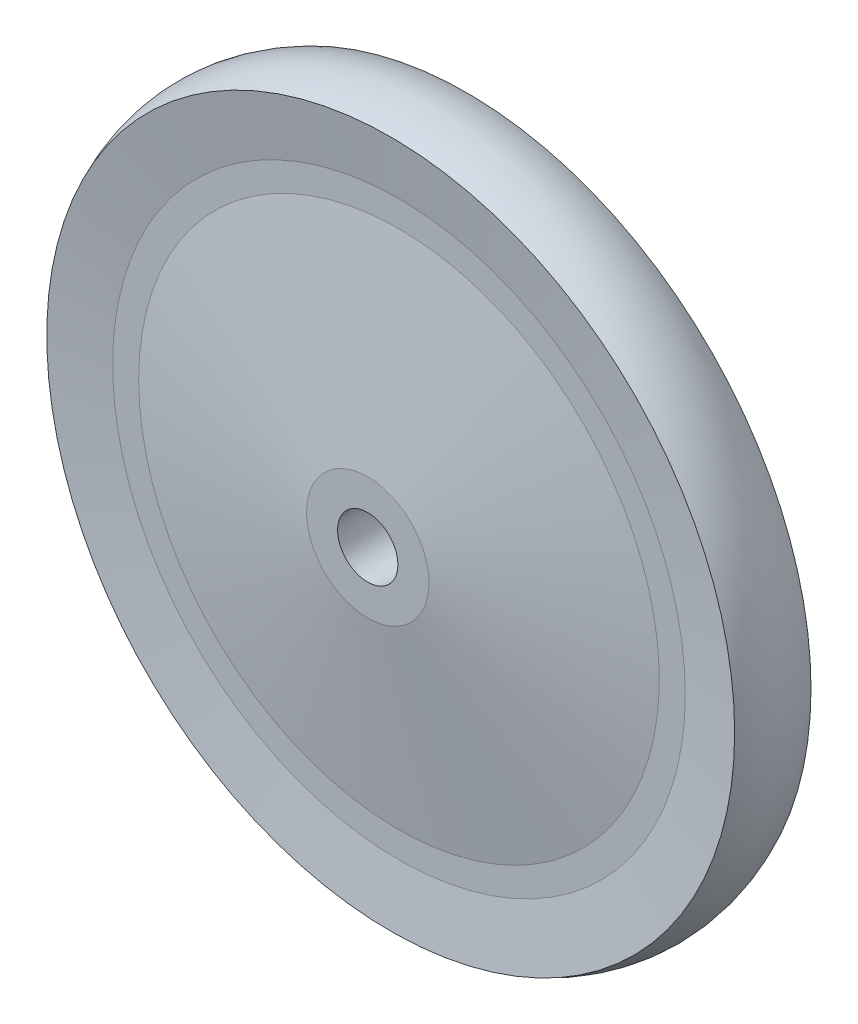
SolidWorks part; units mm, degrees
ref_plane "Front Plane" through (0, 0, 0) normal (0, 0, 1) x (1, 0, 0)
ref_plane "Top Plane" through (0, 0, 0) normal (0, 1, 0) x (1, 0, 0)
ref_plane "Right Plane" through (0, 0, 0) normal (1, 0, 0) x (0, 0, -1)
sketch "Sketch1" plane through (0, 0, 0) normal (1, 0, 0) x (0, 0, -1)
  line L0 (0, 0) -> (144.2834, 0) construction
  line L1 (35.25, 35.25) -> (17.25, 150)
  line L2 (35.25, 35.25) -> (35.25, 17.375)
  line L3 (35.25, 17.375) -> (-35.25, 17.375)
  line L4 (17.25, 150) -> (17.25, 165)
  line L5 (17.25, 165) -> (22, 198.2)
  line L6 (0, 203.2) -> (22, 203.2) construction
  line L7 (0, 0) -> (0, 171.45) construction
  line L8 (22, 203.2) -> (22, 198.2) construction
  line L9 (-35.25, 35.25) -> (-35.25, 17.375)
  line L10 (-35.25, 35.25) -> (-17.25, 150)
  line L11 (-17.25, 150) -> (-17.25, 165)
  line L12 (-17.25, 165) -> (-22, 198.2)
  arc A0 (22, 198.2) -> (-22, 198.2) centre (0, 152.3) ccw
  dimension "D8" = 5
  dimension "D1" = 34.5
  dimension "D2" = 70.5
  dimension "D3" = 70.5
  dimension "D4" = 300
  dimension "D5" = 330
  dimension "D6" = 34.75
  dimension "D7" = 44
  dimension "D9" = 406.4
revolve "Revolve1" add sketch "Sketch1" angle 360 about L0
